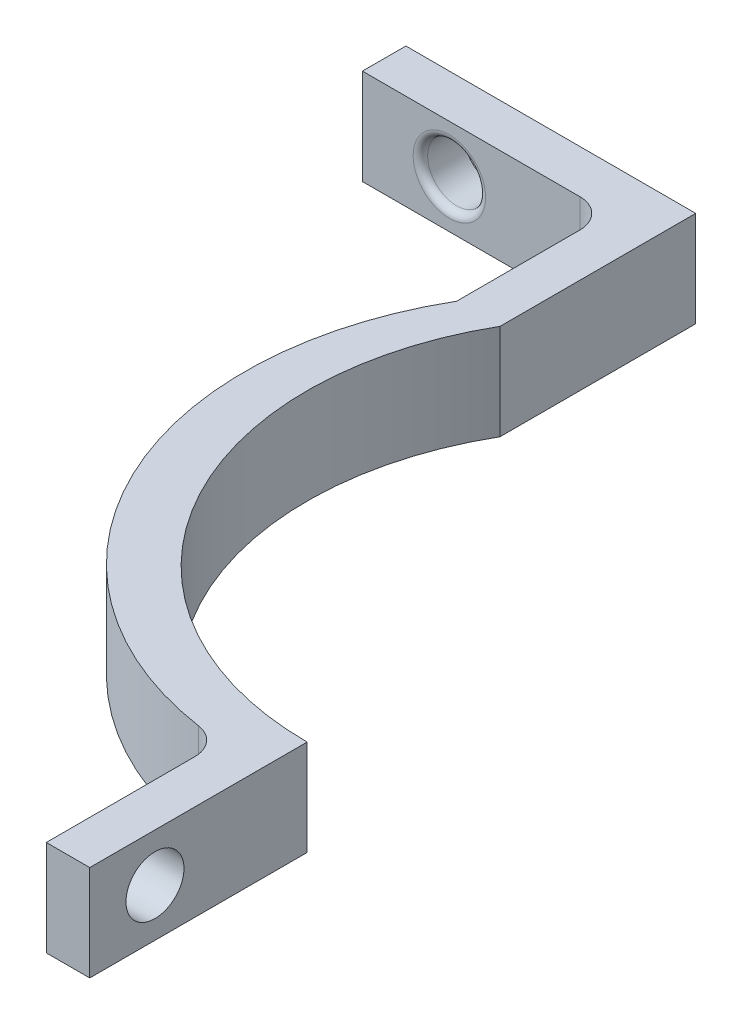
SolidWorks part; units mm, degrees
ref_plane "Front Plane" through (0, 0, 0) normal (0, 0, 1) x (1, 0, 0)
ref_plane "Top Plane" through (0, 0, 0) normal (0, 1, 0) x (1, 0, 0)
ref_plane "Right Plane" through (0, 0, 0) normal (1, 0, 0) x (0, 0, -1)
sketch "Sketch3" plane through (0, 0, 0) normal (0, 1, 0) x (1, 0, 0)
  line L0 (0, 0) -> (0, -3)
  line L2 (0, -15) -> (-3, -15)
  line L3 (-3, -15) -> (-3, -2.9724)
  line L4 (0, 21) -> (0, 31.5)
  line L9 (0, 31.5) -> (-18.1865, 31.5)
  line L10 (-18.1865, 31.5) -> (-21.1865, 31.5)
  line L11 (0, -3) -> (0, -15)
  line L12 (0, 42) -> (0, 45) construction
  line L13 (0, 45) -> (-3, 45) construction
  line L14 (-18.1865, 31.5) -> (-18.1865, 45)
  line L15 (-18.1865, 45) -> (-38.1865, 45)
  line L16 (-38.1865, 45) -> (-38.1865, 42)
  line L17 (-38.1865, 42) -> (-21.1865, 42)
  line L18 (-21.1865, 42) -> (-21.1865, 31.5)
  line L19 (0, 21) -> (0, 0)
  line L20 (0, 42) -> (0, 31.5) construction
  line L21 (-18.1865, 45) -> (-3, 45) construction
  arc A1 (-21.1865, 31.5) -> (0, -3) centre (-1.2889, 19.9639) ccw
  arc A2 (-18.1865, 31.5) -> (0, 42) centre (0, 21) cw construction
  arc A3 (-18.1865, 31.5) -> (0, 0) centre (0, 21) ccw
  point P20 (-2.2636, 48.8742)
  dimension "D1" = 21
  dimension "D7" = 12
  dimension "D10" = 21
  dimension "D14" = 23
  dimension "D2" = 10.5
  dimension "D3" = 3
  dimension "D4" = 3
  dimension "D5" = 3
  dimension "D6" = 3
  dimension "D8" = 20
  dimension "D9" = 3
  dimension "D11" = 42
  dimension "D12" = 21
  dimension "D13" = 18.1865
extrude "Boss-Extrude1" add sketch "Sketch3" along normal blind 6.6 contours A3 L10 A1 L0 | L17 L18 L10 L14 L15 L16 | A1 L3 L2 L11
sketch "Sketch4" plane through (0, 0, -42) normal (0, 0, 1) x (1, 0, 0)
  line L0 (-38.1865, 3.3) -> (-34.1865, 3.3) construction
  line L1 (-38.1865, 6.6) -> (-38.1865, 0) construction
  line L2 (-34.1865, 3.3) -> (-30.1865, 3.3) construction
  circle A0 centre (-32.1865, 3.3) radius 2
  dimension "D1" = 4
  dimension "D2" = 4
extrude "Cut-Extrude1" cut sketch "Sketch4" against normal blind 6.6 contours A0
fillet "Fillet1" radius 2 1 edges at (-21.1865, 3.3, -42)
fillet "Fillet2" radius 0.5 1 edges at (-30.1865, 3.3, -42)
fillet "Fillet3" radius 2 1 edges at (-3, 3.3, 2.9724)
sketch "Sketch5" plane through (-3, 0, 0) normal (-1, 0, 0) x (0, 0, 1)
  line L0 (15, 3.3) -> (12.5, 3.3) construction
  line L1 (15, 6.6) -> (15, 0) construction
  line L2 (12.5, 3.3) -> (8.5, 3.3) construction
  circle A0 centre (10.5, 3.3) radius 2
  dimension "D1" = 2.5
  dimension "D2" = 4
extrude "Cut-Extrude2" cut sketch "Sketch5" against normal blind 6.6
